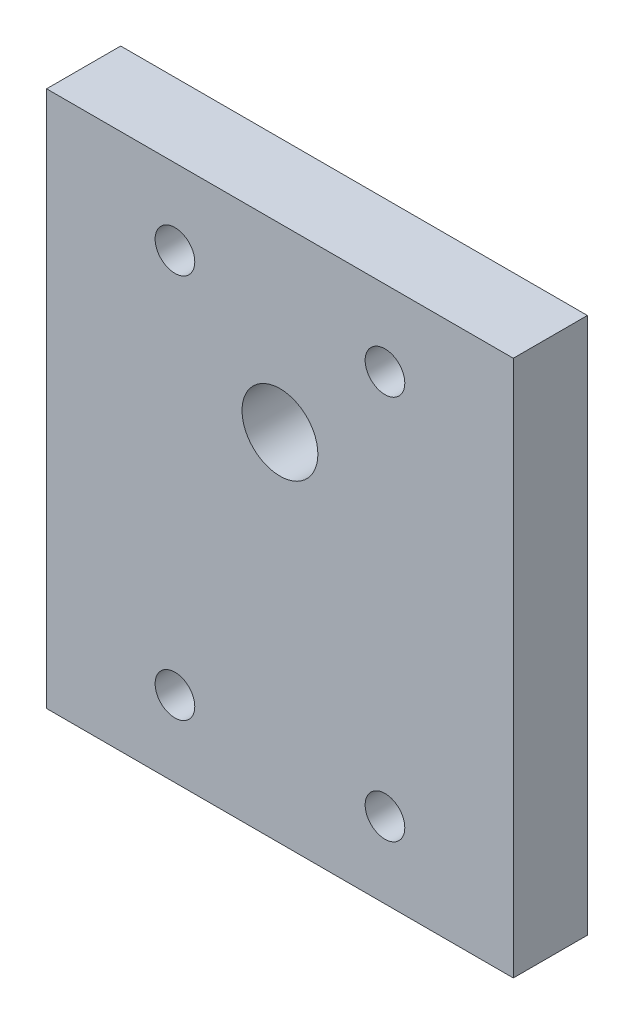
SolidWorks part; units mm, degrees
ref_plane "Front Plane" through (0, 0, 0) normal (0, 0, 1) x (1, 0, 0)
ref_plane "Top Plane" through (0, 0, 0) normal (0, 1, 0) x (1, 0, 0)
ref_plane "Right Plane" through (0, 0, 0) normal (1, 0, 0) x (0, 0, -1)
sketch "Sketch1" plane through (0, 0, 0) normal (0, 0, 1) x (1, 0, 0)
  line B0 (40, 0) -> (0, 0)
  line B1 (40, 0) -> (40, 46)
  line B2 (40, 46) -> (0, 46)
  line B3 (0, 0) -> (0, 46)
  circle B4 centre (29, 39.5) radius 1.7
  circle B5 centre (11, 39.5) radius 1.7
  circle B6 centre (20, 30.5) radius 3.25
  circle B7 centre (11, 6.5) radius 1.7
  circle B8 centre (29, 6.5) radius 1.7
sketch_block_instance "Bottom_IC-1"
sketch_block "Bottom_IC"
extrude "Boss-Extrude1" add sketch "Sketch1" along normal blind 6.35
